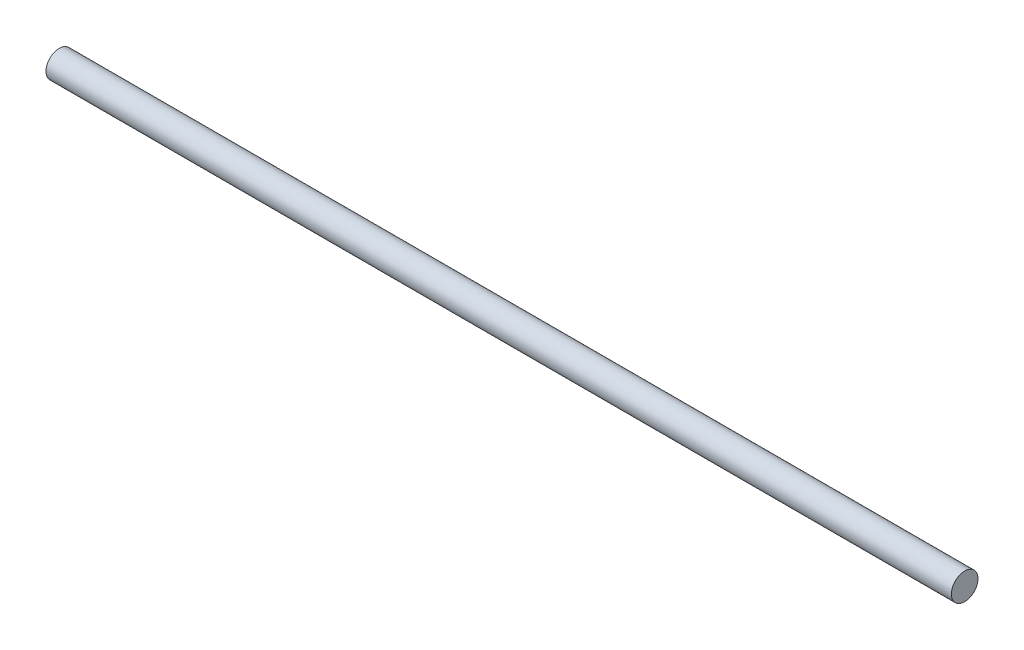
SolidWorks part; units mm, degrees
material "AISI 4340 Steel, annealed"
ref_plane "Front Plane" through (0, 0, 0) normal (0, 0, 1) x (1, 0, 0)
ref_plane "Top Plane" through (0, 0, 0) normal (0, 1, 0) x (1, 0, 0)
ref_plane "Right Plane" through (0, 0, 0) normal (1, 0, 0) x (0, 0, -1)
sketch "Sketch1" plane through (0, 0, 0) normal (1, 0, 0) x (0, 0, -1)
  circle A0 centre (0, 0) radius 5
  dimension "D1" = 10
extrude "Boss-Extrude1" add sketch "Sketch1" along normal mid plane 340 contours A0
